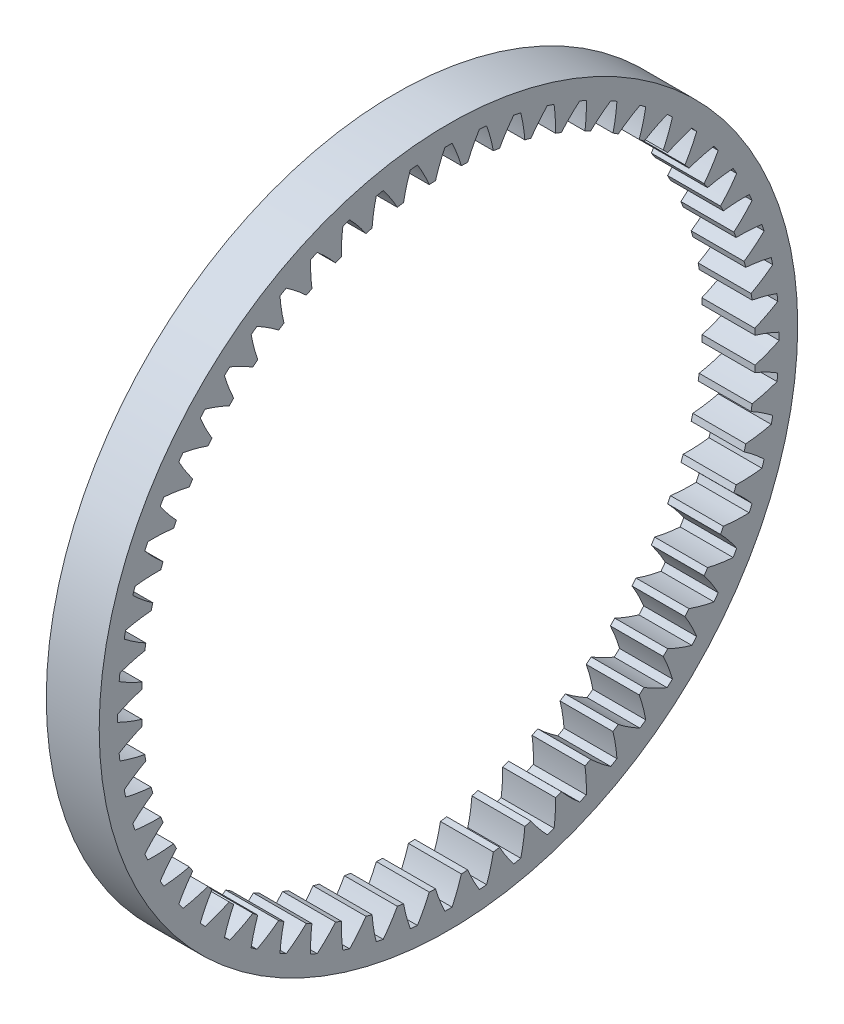
SolidWorks part; units mm, degrees
ref_plane "Plane1" through (0, 0, 0) normal (0, 0, 1) x (1, 0, 0)
ref_plane "Plane2" through (0, 0, 0) normal (0, 1, 0) x (1, 0, 0)
ref_plane "Plane3" through (0, 0, 0) normal (1, 0, 0) x (0, 0, -1)
sketch "HoldingSke" plane through (0, 0, 0) normal (0, 1, 0) x (1, 0, 0)
  line L0 (0, 0) -> (0.5, -0.866)
  line L1 (-15, 0) -> (100, 0) construction
  line L2 (0, 0) -> (-2.1039, 2.3779)
  line L3 (0, 0) -> (-11.863, 4.5341)
  line L4 (0, 0) -> (4.318, 7.479)
  line L5 (0, 0) -> (-23.7986, -8.8762)
  line L6 (0, 0) -> (-10.5278, -7.1032)
  line L7 (-2.1039, 2.3779) -> (3.3635, 27.1825)
  line L8 (-76.2, 3.3779) -> (-54.61, 3.3779)
  line L9 (-71.009, 38.7566) -> (-53.1078, 45.2721)
  line L10 (-76.2, 71.12) -> (104.1128, 71.12)
  line L11 (0, 0) -> (-5, 0)
  line L12 (-76.2, 101.6) -> (-76.162, 101.6)
  line L13 (24.9733, 27.94) -> (52.9518, 28.4284)
  line L14 (24.9733, 27.94) -> (24.9743, 27.94)
  line L15 (24.9733, 27.94) -> (100.4006, 29.5858)
  circle A0 centre (0, 0) radius 33
  circle A1 centre (0, 0) radius 12.7
  circle A2 centre (0, 0) radius 12.7
  dimension "MHD" = 25.4
  dimension "Hub_dia" = 25.4
  dimension "Diameter" = 66
  dimension "Num_teeth" = 60
  dimension "Pitch" = 1
  dimension "Overall_len" = 25.4
  dimension "Show_teeth" = 60
  dimension "Thickness" = 12.7
  dimension "OAL" = 25.4001
  dimension "T_dim" = 21.59
  dimension "Ap" = 20
  dimension "H" = 19.05
  dimension "Pitch_radius" = 180.3128
  dimension "Width" = 5
  dimension "Backlash" = 0.038
  dimension "Addendum_fac" = 1
  dimension "Dedendum_fac" = 1.25
  dimension "Clearance_fac" = 0.25
  dimension "Dedendum_add" = 0.001
  dimension "Module" = 1
sketch "BasProSke" plane through (0, 0, 0) normal (0, 1, 0) x (1, 0, 0)
  line L0 (-10, 0) -> (60, 0) construction
  line L1 (0, 29) -> (0, 33)
  line L2 (0, 29) -> (5, 29)
  line L3 (5, 29) -> (5, 33)
  line L4 (5, 33) -> (0, 33)
  dimension "Diameter" = 66
  dimension "Thickness" = 5
  dimension "Inside_diameter" = 58
revolve "Base-Revolve" add sketch "BasProSke" angle 360 about L0
sketch "TooCutSke" plane through (0, 0, 0) normal (1, 0, 0) x (0, 0, -1)
  line L3 (0.8803, 29.9871) -> (0.8803, 53.6633) construction
  line L4 (0, 0) -> (0, 59.563) construction
  line L5 (0, 0) -> (-3.576, 68.2339) construction
  line L6 (-13.1633, 24.7167) -> (36.4631, 27.3175) construction
  circle A0 centre (0, 0) radius 30 construction
  circle A1 centre (0, 0) radius 31.251 construction
  circle A2 centre (0, 0) radius 25.3717 construction
  circle A3 centre (0, 0) radius 28.9746 construction
  arc A4 (1.2274, 28.9486) -> (0.3395, 31.2492) centre (-13.1633, 24.7167) ccw
  arc A5 (1.2274, 28.9486) -> (-1.2274, 28.9486) centre (0, 0) ccw
  arc A6 (0.3395, 31.2492) -> (-0.3395, 31.2492) centre (0, 0) ccw
  arc A7 (-0.3395, 31.2492) -> (-1.2274, 28.9486) centre (13.1633, 24.7167) ccw
  dimension "Pitch_dia" = 60
  dimension "Base_dia" = 50.7434
  dimension "Root_dia" = 62.502
  dimension "Overcut_dia" = 57.9492
  dimension "Flank_rad" = 15
  dimension "Half_ang" = 3
  dimension "Half_CT" = 0.8803
extrude "ToothCut" cut sketch "TooCutSke" along normal through all
fillet "Breaks" [suppressed] radius 0.1
fillet "RootFillets" [suppressed] radius 0.251
pattern_circular "TeethCuts" count 60 every 6 about axis through (-10, 0, 0) along (1, 0, 0) of "RootFillets", "Breaks", "ToothCut"
equation "' \"Module@HoldingSke\" = 6.35"
equation "' \"Num_teeth@HoldingSke\" = 24"
equation "' \"Ap@HoldingSke\" =  14.5"
equation "' \"Ap@HoldingSke\" = 14.5"
equation "' \"Width@HoldingSke\" = 12"
equation "' \"Diameter@HoldingSke\" = 8 * 25.4"
equation "' \"Show_teeth@HoldingSke\" = 100"
equation "' \"Backlash@HoldingSke\" = 0.009 * 25.4"
equation "' \"Addendum_fac@HoldingSke\" = 1.0"
equation "' \"Dedendum_fac@HoldingSke\" = 1.25"
equation "' \"Dedendum_add@HoldingSke\" = 0.00005 * 25.4"
equation "' \"Clearance_fac@HoldingSke\" = 0.25"
equation "\"Pitch@HoldingSke\" = 1 / \"Module@HoldingSke\" "
equation "\"Overcut_dia@TooCutSke\" = (\"Num_teeth@HoldingSke\" - 2 * \"Addendum_fac@HoldingSke\") / \"Pitch@HoldingSke\" - 0.002 * 25.4"
equation "\"Pitch_dia@TooCutSke\" = \"Num_teeth@HoldingSke\" / \"Pitch@HoldingSke\""
equation "\"Base_dia@TooCutSke\" = \"Num_teeth@HoldingSke\" / \"Pitch@HoldingSke\" * cos((\"Ap@HoldingSke\"  * 3.14159265 / 180)) * 0.90"
equation "\"Root_dia@TooCutSke\" = \"Num_teeth@HoldingSke\"  / \"Pitch@HoldingSke\" + 2 *  \"Dedendum_fac@HoldingSke\"/ \"Pitch@HoldingSke\" + \"Dedendum_add@HoldingSke\" * 2"
equation "\"Half_ang@TooCutSke\" = 180 / \"Num_teeth@HoldingSke\""
equation "\"Half_CT@TooCutSke\" = \"Num_teeth@HoldingSke\" / \"Pitch@HoldingSke\" * sin((3.14159265 / 2 / \"Num_teeth@HoldingSke\")) / 2 + 10 * \"Backlash@HoldingSke\" / 4"
equation "\"Flank_rad@TooCutSke\" = \"Num_teeth@HoldingSke\" / \"Pitch@HoldingSke\" / 4"
equation "\"Radius@RootFillets\"= \"Clearance_fac@HoldingSke\" / \"Pitch@HoldingSke\" + \"Dedendum_add@HoldingSke\""
equation "\"Break_rad@Breaks\" = 0.02 / \"Pitch@HoldingSke\" * 5"
equation "\"Num_teeth@TeethCuts\" = int( \"Show_teeth@HoldingSke\" ) + 1"
equation "\"Num_teeth@TeethCuts\" = ((sgn( \"Num_teeth@TeethCuts\" - \"Num_teeth@HoldingSke\" )-1)*( \"Num_teeth@TeethCuts\" - \"Num_teeth@HoldingSke\" ))/-2+ \"Num_teeth@HoldingSke\""
equation "\"Num_teeth@TeethCuts\" = ((sgn( \"Num_teeth@TeethCuts\" - 2.0)+1)*( \"Num_teeth@TeethCuts\" - 2.0))/2 +2.0"
equation "\"Angle@TeethCuts\" = 360.0 / \"Num_teeth@HoldingSke\""
equation "\"Diameter@BasProSke\" = \"Num_teeth@HoldingSke\"  / \"Pitch@HoldingSke\" + 2 *  \"Dedendum_fac@HoldingSke\"/ \"Pitch@HoldingSke\" + \"Dedendum_add@HoldingSke\" * 2 + 0.002 * 25.4"
equation "\"Diameter@BasProSke\" = ((sgn( \"Diameter@BasProSke\"  - \"Diameter@HoldingSke\" )+1)*( \"Diameter@BasProSke\"  - \"Diameter@HoldingSke\" ))/2 + \"Diameter@HoldingSke\""
equation "\"Inside_diameter@BasProSke\" =  (\"Num_teeth@HoldingSke\" - 2 * \"Addendum_fac@HoldingSke\") / \"Pitch@HoldingSke\" "
equation "\"Thickness@BasProSke\"  = \"Width@HoldingSke\""
